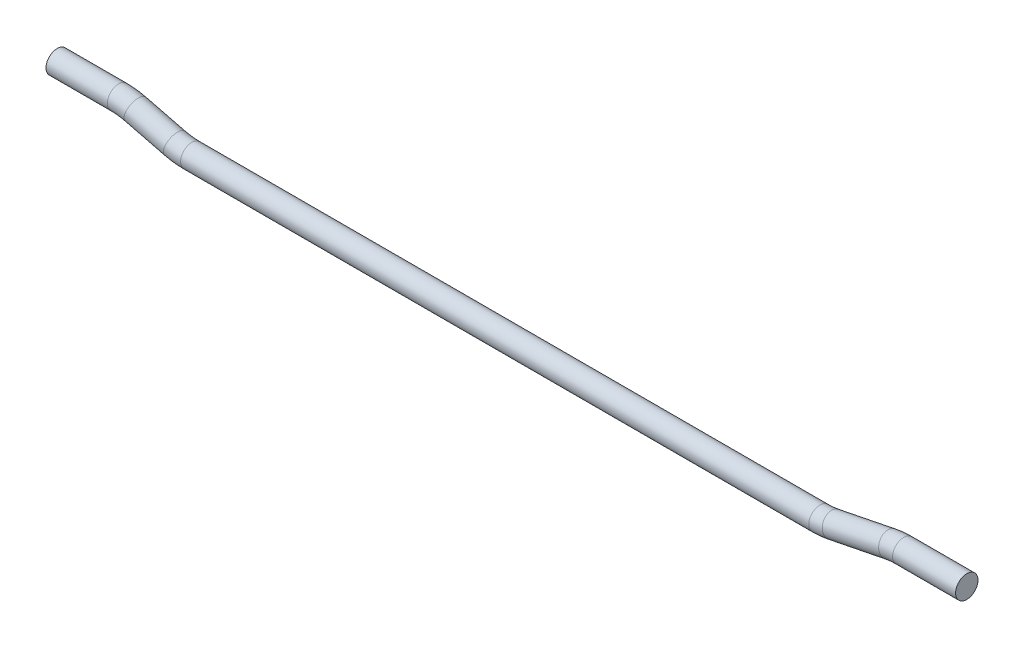
SolidWorks part; units mm, degrees
ref_plane "Front Plane" through (0, 0, 0) normal (0, 0, 1) x (1, 0, 0)
ref_plane "Top Plane" through (0, 0, 0) normal (0, 1, 0) x (1, 0, 0)
ref_plane "Right Plane" through (0, 0, 0) normal (1, 0, 0) x (0, 0, -1)
sketch "Sketch1" plane through (0, 0, 0) normal (1, 0, 0) x (0, 0, -1)
  circle A0 centre (0, 0) radius 0.8
  dimension "D1" = 1.6
sketch "Sketch2" plane through (0, 0, 0) normal (0, 0, 1) x (1, 0, 0)
  line L0 (0, 0) -> (4.385, 0)
  line L1 (0, -0.8) -> (0, 0.8) construction
  line L2 (5.5967, -0.149) -> (8.4068, -0.851)
  line L3 (9.6185, -1) -> (54.5049, -1)
  line L4 (55.4855, -0.9029) -> (59.5145, -0.0971)
  line L5 (60.4951, 0) -> (65, 0)
  arc A0 (59.5145, -0.0971) -> (60.4951, 0) centre (60.4951, -5) cw
  arc A1 (54.5049, -1) -> (55.4855, -0.9029) centre (54.5049, 4) ccw
  arc A2 (8.4068, -0.851) -> (9.6185, -1) centre (9.6185, 4) ccw
  arc A3 (5.5967, -0.149) -> (4.385, 0) centre (4.385, -5) ccw
  point P10 (60, 0)
  point P13 (55, -1)
  point P16 (9.0035, -1)
  point P19 (5, 0)
  dimension "D7" = 5
  dimension "D8" = 5
  dimension "D1" = 65
  dimension "D2" = 5
  dimension "D3" = 5
  dimension "D4" = 1
  dimension "D5" = 4.0035
  dimension "D6" = 5
sweep "Sweep1" add profiles "Sketch1" path "Sketch2"
